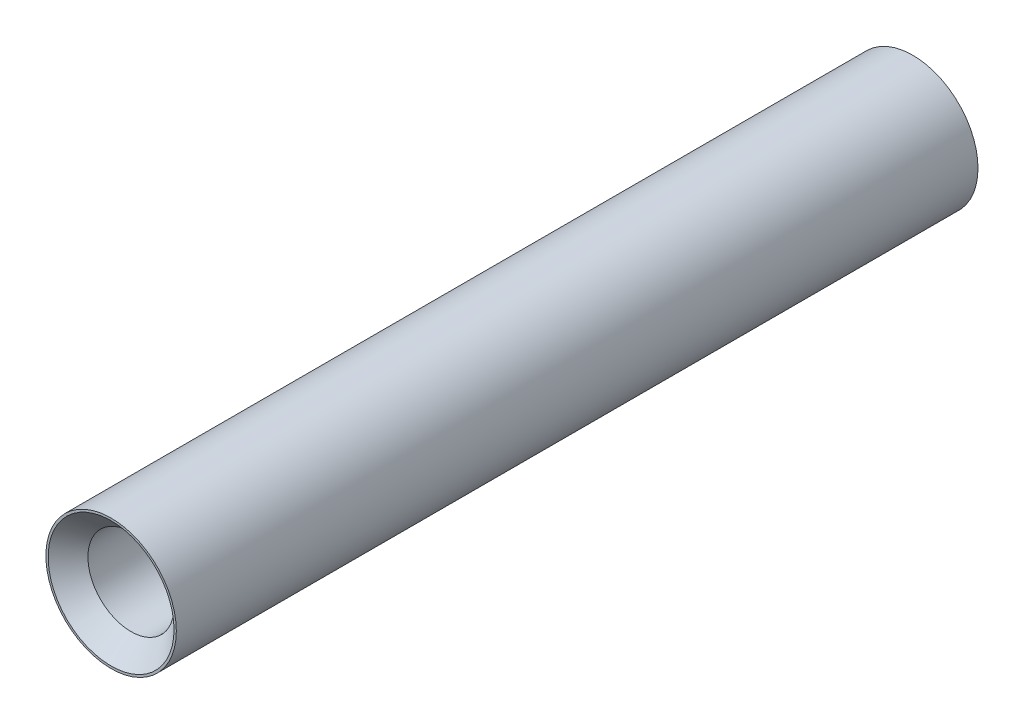
SolidWorks part; units mm, degrees
ref_plane "Ön Düzlem" through (0, 0, 0) normal (0, 0, 1) x (1, 0, 0)
ref_plane "Üst Düzlem" through (0, 0, 0) normal (0, 1, 0) x (1, 0, 0)
ref_plane "Sağ Düzlem" through (0, 0, 0) normal (1, 0, 0) x (0, 0, -1)
sketch "Sketch1" plane through (0, 0, 0) normal (0, 0, 1) x (1, 0, 0)
  circle A0 centre (0, 0) radius 3.5
  dimension "D1" = 7
extrude "Boss-Extrude1" add sketch "Sketch1" along normal blind 43.02
hole_wizard "#12-28 Tapped Hole1" positions "3DSketch11" profile "Sketch7" tap size "#12-28" standard "ANSI Inch"
sketch3d "3DSketch11"
  line L0 (0, 0, 43.02) -> (0, 0, 0) construction
  point P0 (0, 0, 0)
  point P3 (0, 0, 0)
  point P5 (0, 0, 0)
  point P7 (0, 0, 43.02)
sketch "Sketch7" plane through (0, 0, 43.02) normal (1, 0, 0) x (0, -1, 0)
  line L0 (0, 0) -> (0, 15.0788)
  line L1 (0, 15.0788) -> (2.3114, 13.69)
  line L2 (2.3114, 13.69) -> (2.3114, 1.0668)
  line L3 (2.3114, 1.0668) -> (3.3782, 0)
  line L5 (3.3782, 0) -> (0, 0)
  line L6 (-2.3114, 1.0668) -> (-3.3782, 0) construction
  line L10 (0, 15.0788) -> (-2.3114, 13.69) construction
  line L11 (0, -6.35) -> (0, 107.95) construction
  dimension "Tap Drill Dia." = 4.6228
  dimension "Tap Drill Depth" = 13.69
  dimension "Near C'Sink Dia." = 6.7564
  dimension "Near C'Sink Angle" = 90
  dimension "Drill Angle" = 118
cosmetic thread "Hole Thread9" parameters "D1"=10.97, "D2"=5.4864
cosmetic thread "Hole Thread10" parameters "D1"=10.97, "D2"=5.4864
cosmetic thread "Hole Thread11" parameters "D1"=10.97, "D2"=5.4864
cosmetic thread "Hole Thread12" parameters "D1"=10.97, "D2"=5.4864
ref_plane "Plane2" through (0, 0, 21.51) normal (0, 0, 1) x (1, 0, 0)
mirror "Mirror1" about plane through (0, 0, 21.51) normal (0, 0, 1) of "#12-28 Tapped Hole1"
